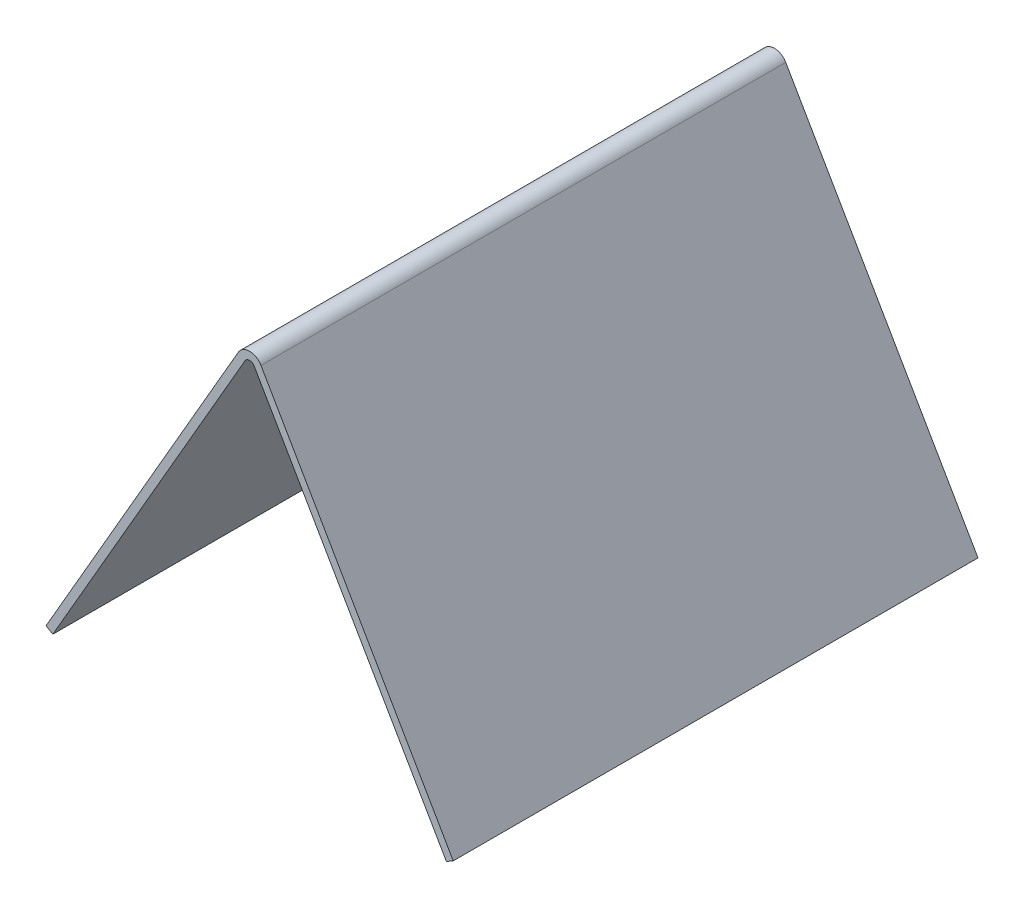
SolidWorks part; units mm, degrees
ref_plane "Front Plane" through (0, 0, 0) normal (0, 0, 1) x (1, 0, 0)
ref_plane "Top Plane" through (0, 0, 0) normal (0, 1, 0) x (1, 0, 0)
ref_plane "Right Plane" through (0, 0, 0) normal (1, 0, 0) x (0, 0, -1)
sketch "Sketch1" plane through (0, 0, 0) normal (0, 0, 1) x (1, 0, 0)
  line L0 (0, 123.3774) -> (0, 0) construction
  line L1 (-1.7321, 126.9038) -> (-75, 0)
  line L2 (-75, 0) -> (-77.5981, 1.5)
  line L3 (-77.5981, 1.5) -> (-4.3301, 128.4038)
  line L4 (-80.229, 0) -> (80.8253, 0) construction
  line L5 (1.7321, 126.9038) -> (75, 0)
  line L6 (77.5981, 1.5) -> (4.3301, 128.4038)
  line L7 (75, 0) -> (77.5981, 1.5)
  arc A0 (1.7321, 126.9038) -> (-1.7321, 126.9038) centre (0, 125.9038) ccw
  arc A1 (4.3301, 128.4038) -> (-4.3301, 128.4038) centre (0, 125.9038) ccw
  point P15 (0, 129.9038)
  dimension "D4" = 2
  dimension "D1" = 30
  dimension "D2" = 3
  dimension "D3" = 150
extrude "Boss-Extrude1" add sketch "Sketch1" along normal blind 200
